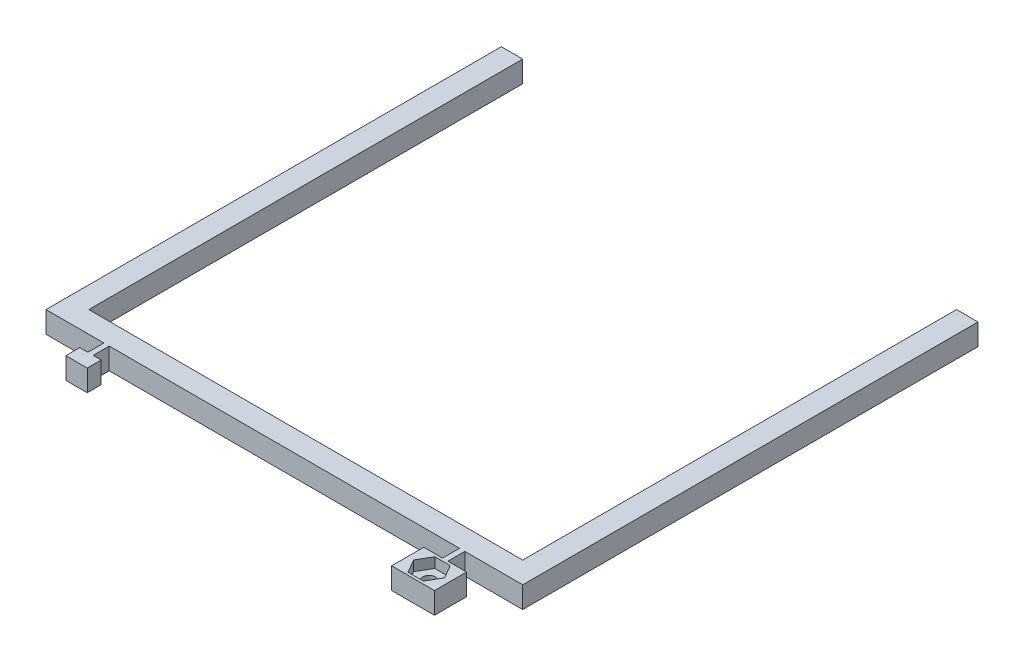
SolidWorks part; units mm, degrees
ref_plane "Front Plane" through (0, 0, 0) normal (0, 0, 1) x (1, 0, 0)
ref_plane "Top Plane" through (0, 0, 0) normal (0, 1, 0) x (1, 0, 0)
ref_plane "Right Plane" through (0, 0, 0) normal (1, 0, 0) x (0, 0, -1)
sketch "Sketch1" plane through (0, 0, 0) normal (0, 1, 0) x (1, 0, 0)
  line L0 (41.5205, 0) -> (-41.5205, 0)
  line L1 (-41.5205, 0) -> (-41.5205, -3.81)
  line L2 (-41.5205, -3.81) -> (-39.6155, -3.81)
  line L3 (-39.6155, -3.81) -> (-39.6155, -7.112)
  line L4 (-39.6155, -7.112) -> (-44.6955, -7.112)
  line L5 (-44.6955, -7.112) -> (-44.6955, -3.81)
  line L6 (-44.6955, -3.81) -> (-42.7905, -3.81)
  line L7 (-42.7905, -3.81) -> (-42.7905, 0)
  line L8 (-42.7905, 0) -> (-56.515, 0)
  line L9 (-56.515, 0) -> (-56.515, 107.95)
  line L10 (-56.515, 107.95) -> (-51.435, 107.95)
  line L11 (-51.435, 107.95) -> (-51.435, 5.08)
  line L12 (-51.435, 5.08) -> (51.435, 5.08)
  line L13 (0, 0) -> (0, 73.9855) construction
  line L14 (51.435, 107.95) -> (51.435, 5.08)
  line L15 (56.515, 107.95) -> (51.435, 107.95)
  line L16 (56.515, 0) -> (56.515, 107.95)
  line L17 (42.7905, 0) -> (56.515, 0)
  line L25 (41.5205, 0) -> (41.5205, -4.0198)
  line L26 (41.5205, -4.0198) -> (37.0755, -4.0198)
  line L27 (37.0755, -4.0198) -> (37.0755, -11.6398)
  line L28 (37.0755, -11.6398) -> (47.2355, -11.6398)
  line L29 (47.2355, -11.6398) -> (47.2355, -4.0198)
  line L30 (47.2355, -4.0198) -> (42.7905, -4.0198)
  line L31 (42.7905, -4.0198) -> (42.7905, 0)
  point P16 (0, 5.08)
  dimension "D1" = 5.08
  dimension "D2" = 102.87
  dimension "D3" = 107.95
  dimension "D4" = 5.08
  dimension "D5" = 3.81
  dimension "D6" = 1.27
  dimension "D7" = 102.87
  dimension "D8" = 10.16
  dimension "D9" = 7.62
  dimension "D10" = 13.7245
  dimension "D11" = 11.6398
  dimension "D12" = 7.112
extrude "Boss-Extrude1" add sketch "Sketch1" along normal blind 5.08
sketch "Sketch2" plane through (0, 5.08, 0) normal (0, 1, 0) x (1, 0, 0)
  line L0 (37.0755, -4.0198) -> (47.2355, -11.6398) construction
  line L1 (47.2355, -11.6398) -> (47.2355, -4.0198) construction
  line L2 (47.2355, -4.0198) -> (42.7905, -4.0198) construction
  line L3 (47.2355, -11.6398) -> (47.2355, -4.0198) construction
  line L4 (47.2355, -4.0198) -> (37.0755, -11.6398) construction
  line L6 (40.3225, -4.6548) -> (38.4894, -7.8298)
  line L7 (38.4894, -7.8298) -> (40.3225, -11.0048)
  line L8 (40.3225, -11.0048) -> (43.9886, -11.0048)
  line L9 (43.9886, -11.0048) -> (45.8217, -7.8298)
  line L10 (45.8217, -7.8298) -> (43.9886, -4.6548)
  line L11 (43.9886, -4.6548) -> (40.3225, -4.6548)
  circle A0 centre (42.1555, -7.8298) radius 3.175 construction
  dimension "D1" = 6.35
extrude "Cut-Extrude1" cut sketch "Sketch2" against normal blind 2.413
sketch "Sketch8" plane through (0, 2.667, 0) normal (0, 1, 0) x (1, 0, 0)
  line L0 (43.9886, -4.6548) -> (40.3225, -11.0048) construction
  line L1 (43.9886, -11.0048) -> (40.3225, -4.6548) construction
  circle A0 centre (42.1555, -7.8298) radius 1.524
extrude "Cut-Extrude2" cut sketch "Sketch8" against normal up to surface (2.667 mm away) up to face at (0, 0, -15.5474)
